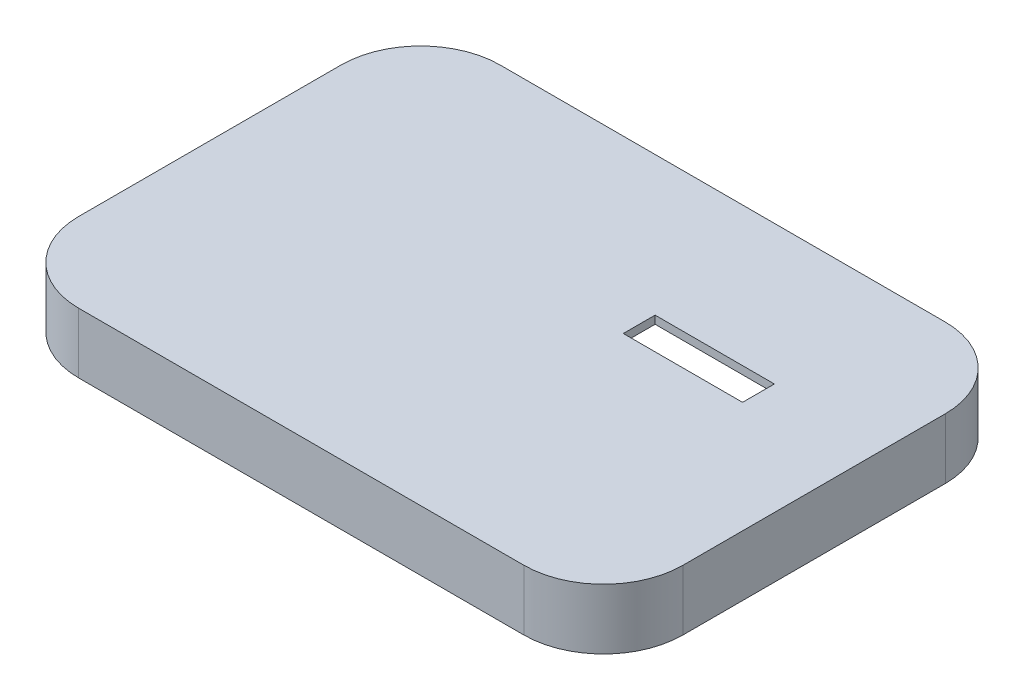
SolidWorks part; units mm, degrees
ref_plane "Front Plane" through (0, 0, 0) normal (0, 0, 1) x (1, 0, 0)
ref_plane "Top Plane" through (0, 0, 0) normal (0, 1, 0) x (1, 0, 0)
ref_plane "Right Plane" through (0, 0, 0) normal (1, 0, 0) x (0, 0, -1)
sketch "Sketch1" plane through (0, 0, 0) normal (0, 1, 0) x (1, 0, 0)
  line L1 (-28, -26.5) -> (28, -26.5)
  line L2 (-38, -16.5) -> (-38, 16.5)
  line L3 (-28, 26.5) -> (28, 26.5)
  line L4 (38, -16.5) -> (38, 16.5)
  line L5 (-38, -26.5) -> (38, 26.5) construction
  line L6 (-38, 26.5) -> (38, -26.5) construction
  line L7 (9, 9) -> (24, 9)
  line L8 (9, 9) -> (9, 5)
  line L9 (9, 5) -> (24, 5)
  line L10 (24, 9) -> (24, 5)
  arc A0 (-38, 16.5) -> (-28, 26.5) centre (-28, 16.5) cw
  arc A1 (38, 16.5) -> (28, 26.5) centre (28, 16.5) ccw
  arc A2 (28, -26.5) -> (38, -16.5) centre (28, -16.5) ccw
  arc A3 (-38, -16.5) -> (-28, -26.5) centre (-28, -16.5) ccw
  point P0 (0, 0)
  dimension "D3" = 10
  dimension "D4" = 10
  dimension "D5" = 10
  dimension "D6" = 10
  dimension "D1" = 53
  dimension "D2" = 76
  dimension "D7" = 17.5
  dimension "D8" = 14
  dimension "D9" = 15
  dimension "D10" = 4
extrude "Boss-Extrude1" add sketch "Sketch1" along normal blind 1
sketch "Sketch2" plane through (0, 0, 0) normal (0, -1, 0) x (1, 0, 0)
  line L0 (28, 25.5) -> (-28, 25.5)
  line L1 (-37, 16.5) -> (-37, -16.5)
  line L2 (-28, -25.5) -> (28, -25.5)
  line L3 (37, -16.5) -> (37, 16.5)
  line L4 (-28, -26.5) -> (28, -26.5)
  line L5 (38, -16.5) -> (38, 16.5)
  line L6 (28, 26.5) -> (-28, 26.5)
  line L7 (-38, 16.5) -> (-38, -16.5)
  line L8 (-28, -26.5) -> (28, -26.5)
  line L9 (38, -16.5) -> (38, 16.5)
  line L10 (28, 26.5) -> (-28, 26.5)
  line L11 (-38, 16.5) -> (-38, -16.5)
  arc A0 (-28, 25.5) -> (-37, 16.5) centre (-28, 16.5) ccw
  arc A1 (-37, -16.5) -> (-28, -25.5) centre (-28, -16.5) ccw
  arc A2 (28, -25.5) -> (37, -16.5) centre (28, -16.5) ccw
  arc A3 (37, 16.5) -> (28, 25.5) centre (28, 16.5) ccw
  arc A4 (-38, -16.5) -> (-28, -26.5) centre (-28, -16.5) ccw
  arc A5 (28, -26.5) -> (38, -16.5) centre (28, -16.5) ccw
  arc A6 (38, 16.5) -> (28, 26.5) centre (28, 16.5) ccw
  arc A7 (-28, 26.5) -> (-38, 16.5) centre (-28, 16.5) ccw
  arc A8 (-38, -16.5) -> (-28, -26.5) centre (-28, -16.5) ccw
  arc A9 (28, -26.5) -> (38, -16.5) centre (28, -16.5) ccw
  arc A10 (38, 16.5) -> (28, 26.5) centre (28, 16.5) ccw
  arc A11 (-28, 26.5) -> (-38, 16.5) centre (-28, 16.5) ccw
  dimension "D1" = 0
  dimension "D2" = 1
extrude "Boss-Extrude2" add sketch "Sketch2" along normal blind 6
sketch "Sketch3" plane through (0, 0, 0) normal (0, -1, 0) x (1, 0, 0)
  line L0 (37, 0) -> (-37, 0) construction
  line L1 (37, -16.5) -> (37, 16.5) construction
  line L2 (-37, 16.5) -> (-37, -16.5) construction
  line L3 (-28, -25.5) -> (28, -25.5) construction
  line L4 (5, -25.5) -> (-5, -25.5)
  line L5 (5, -25.5) -> (5, -22.5)
  line L6 (5, -22.5) -> (-5, -22.5)
  line L7 (-5, -25.5) -> (-5, -22.5)
  line L8 (0, -55) -> (0, 55) construction
  line L9 (-5, 25.5) -> (-5, 22.5)
  line L10 (5, 25.5) -> (-5, 25.5)
  line L11 (5, 25.5) -> (5, 22.5)
  line L12 (5, 22.5) -> (-5, 22.5)
  dimension "D1" = 10
  dimension "D2" = 5
  dimension "D3" = 3
extrude "Boss-Extrude3" add sketch "Sketch3" along normal blind 3.5
sketch "Sketch4" plane through (0, -6, 0) normal (0, -1, 0) x (1, 0, 0)
  line L4 (-28, -26.5) -> (28, -26.5)
  line L5 (38, -16.5) -> (38, 16.5)
  line L6 (28, 26.5) -> (-28, 26.5)
  line L7 (-38, 16.5) -> (-38, -16.5)
  line L8 (-28, -26.5) -> (28, -26.5)
  line L9 (38, -16.5) -> (38, 16.5)
  line L10 (28, 26.5) -> (-28, 26.5)
  line L11 (-38, 16.5) -> (-38, -16.5)
  line L34 (28, 25) -> (-28, 25)
  line L35 (-36.5, 16.5) -> (-36.5, -16.5)
  line L36 (-28, -25) -> (28, -25)
  line L37 (36.5, -16.5) -> (36.5, 16.5)
  line L38 (28, 25) -> (-28, 25)
  line L39 (-36.5, 16.5) -> (-36.5, -16.5)
  line L40 (-28, -25) -> (28, -25)
  line L41 (36.5, -16.5) -> (36.5, 16.5)
  arc A4 (-38, -16.5) -> (-28, -26.5) centre (-28, -16.5) ccw
  arc A5 (28, -26.5) -> (38, -16.5) centre (28, -16.5) ccw
  arc A6 (38, 16.5) -> (28, 26.5) centre (28, 16.5) ccw
  arc A7 (-28, 26.5) -> (-38, 16.5) centre (-28, 16.5) ccw
  arc A8 (-38, -16.5) -> (-28, -26.5) centre (-28, -16.5) ccw
  arc A9 (28, -26.5) -> (38, -16.5) centre (28, -16.5) ccw
  arc A10 (38, 16.5) -> (28, 26.5) centre (28, 16.5) ccw
  arc A11 (-28, 26.5) -> (-38, 16.5) centre (-28, 16.5) ccw
  arc A27 (36.5, 16.5) -> (28, 25) centre (28, 16.5) ccw
  arc A28 (-28, 25) -> (-36.5, 16.5) centre (-28, 16.5) ccw
  arc A29 (-36.5, -16.5) -> (-28, -25) centre (-28, -16.5) ccw
  arc A30 (28, -25) -> (36.5, -16.5) centre (28, -16.5) ccw
  arc A31 (36.5, 16.5) -> (28, 25) centre (28, 16.5) ccw
  arc A32 (-28, 25) -> (-36.5, 16.5) centre (-28, 16.5) ccw
  arc A33 (-36.5, -16.5) -> (-28, -25) centre (-28, -16.5) ccw
  arc A34 (28, -25) -> (36.5, -16.5) centre (28, -16.5) ccw
  dimension "D1" = 0
  dimension "D2" = 0.5
extrude "Boss-Extrude4" add sketch "Sketch4" along normal blind 0.6
sketch "Sketch5" plane through (0, 0, 0) normal (0, -1, 0) x (1, 0, 0)
  line L0 (37, 0) -> (-37, 0) construction
  line L1 (37, -16.5) -> (37, 16.5) construction
  line L2 (-37, 16.5) -> (-37, -16.5) construction
  line L4 (37, 5) -> (34, 5)
  line L5 (37, 5) -> (37, -5)
  line L6 (37, -5) -> (34, -5)
  line L7 (34, 5) -> (34, -5)
  line L8 (0, 22.5) -> (0, -23.0426) construction
  line L9 (-5, 22.5) -> (5, 22.5) construction
  line L10 (-37, 5) -> (-34, 5)
  line L11 (-37, 5) -> (-37, -5)
  line L12 (-37, -5) -> (-34, -5)
  line L13 (-34, 5) -> (-34, -5)
  dimension "D1" = 3
  dimension "D2" = 10
  dimension "D3" = 5
extrude "Boss-Extrude5" add sketch "Sketch5" along normal blind 3.5
